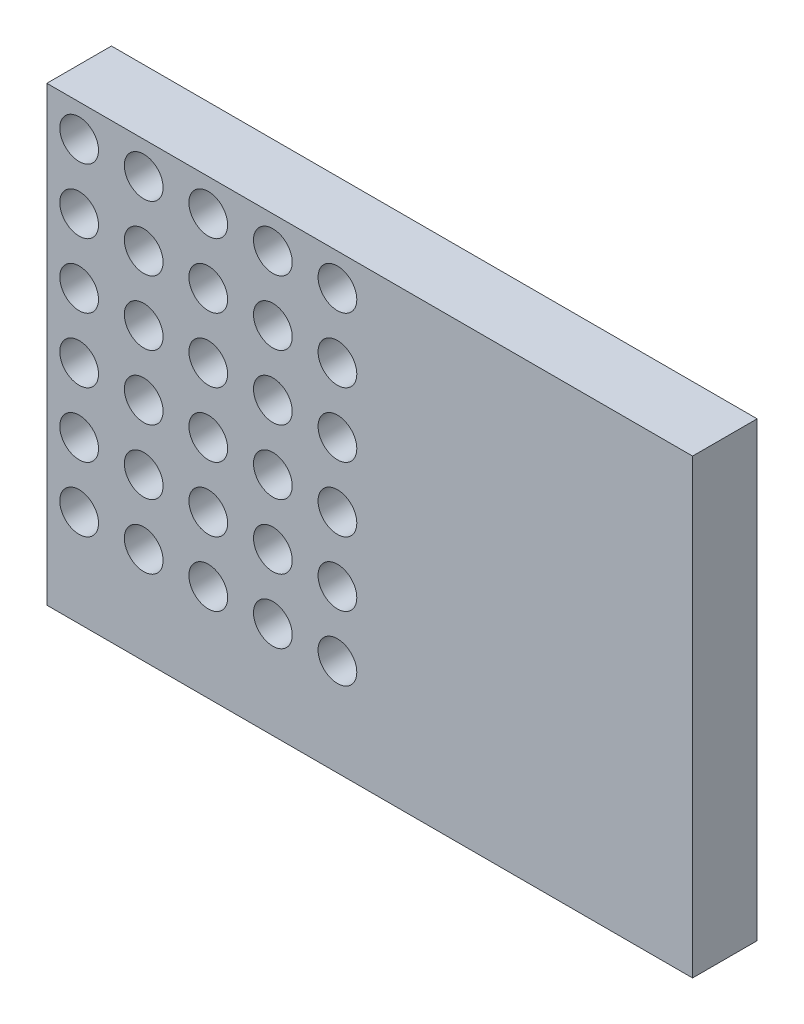
SolidWorks part; units mm, degrees
ref_plane "前视基准面" through (0, 0, 0) normal (0, 0, 1) x (1, 0, 0)
ref_plane "上视基准面" through (0, 0, 0) normal (0, 1, 0) x (1, 0, 0)
ref_plane "右视基准面" through (0, 0, 0) normal (1, 0, 0) x (0, 0, -1)
sketch "草图1" plane through (0, 0, 0) normal (0, 0, 1) x (1, 0, 0)
  line L1 (-50, 35) -> (50, 35)
  line L2 (-50, 35) -> (-50, -35)
  line L3 (-50, -35) -> (50, -35)
  line L4 (50, 35) -> (50, -35)
  line L5 (-50, 35) -> (50, -35) construction
  line L6 (-50, -35) -> (50, 35) construction
  point P0 (0, 0)
  dimension "D1" = 70
  dimension "D2" = 100
extrude "凸台-拉伸1" add sketch "草图1" along normal mid plane 10
sketch "草图2" plane through (0, 0, 5) normal (0, 0, 1) x (1, 0, 0)
  line L0 (50, 35) -> (-50, 35) construction
  line L2 (-50, 35) -> (-50, -35) construction
  circle A0 centre (-45, 30) radius 3
  dimension "D1" = 5
  dimension "D2" = 5
extrude "切除-拉伸1" cut sketch "草图2" against normal blind 10
pattern_linear "阵列(线性)1" count 5 spacing 10 along (1, 0, 0) count 6 spacing 10 along (0, -1, 0) of "切除-拉伸1"
